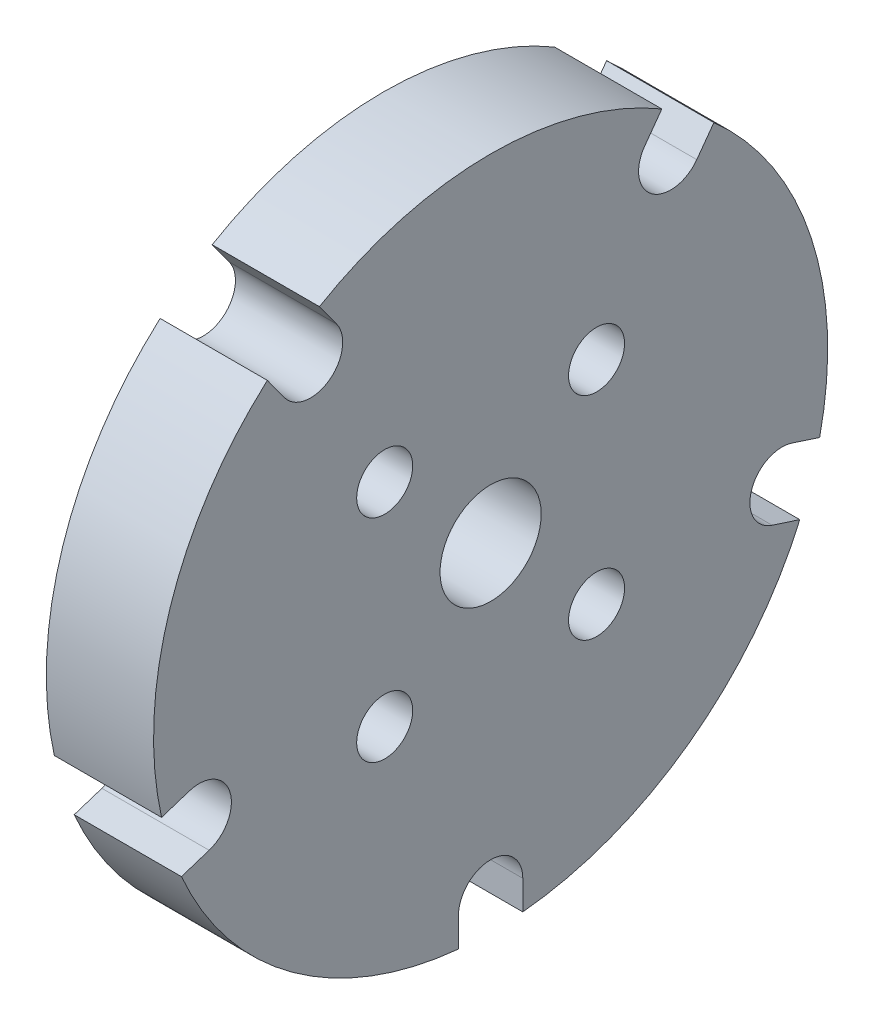
SolidWorks part; units mm, degrees
ref_plane "Plan de face" through (0, 0, 0) normal (0, 0, 1) x (1, 0, 0)
ref_plane "Plan de dessus" through (0, 0, 0) normal (0, 1, 0) x (1, 0, 0)
ref_plane "Plan de droite" through (0, 0, 0) normal (1, 0, 0) x (0, 0, -1)
sketch "Esquisse1" plane through (0, 0, 0) normal (1, 0, 0) x (0, 0, -1)
  circle A0 centre (0, 0) radius 22
  dimension "D1" = 44
extrude "Boss.-Extru.1" add sketch "Esquisse1" along normal blind 7
sketch "Esquisse5" plane through (7, 0, 0) normal (1, 0, 0) x (0, 0, -1)
  line L0 (0, -20) -> (0, -24) construction
  line L1 (2.1, -20) -> (2.1, -24)
  line L2 (-2.1, -20) -> (-2.1, -24)
  line L3 (0, 0) -> (0, -20) construction
  arc A0 (2.1, -20) -> (-2.1, -20) centre (0, -20) ccw
  arc A1 (-2.1, -24) -> (2.1, -24) centre (0, -24) ccw
  circle A2 centre (0, 0) radius 22 construction
  point P3 (0, -22)
  dimension "D2" = 4.2
  dimension "D1" = 20
extrude "Enlèv. mat.-Extru.1" cut sketch "Esquisse5" against normal up to next
pattern_circular "Répétition circulaire1" count 5 over 360 about axis through (0, 0, 0) along (1, 0, 0) of "Enlèv. mat.-Extru.1"
sketch "Esquisse6" plane through (7, 0, 0) normal (1, 0, 0) x (0, 0, -1)
  circle A0 centre (0, 0) radius 3.3
  dimension "D1" = 6.6
extrude "Enlèv. mat.-Extru.2" cut sketch "Esquisse6" against normal up to next
hole_wizard "Chambrage pour vis à tête ronde bombée #61" positions "Esquisse7" profile "Esquisse8" counterbore size "#6" standard "Ansi Inch" end condition through all
sketch "Esquisse7" plane through (0, 0, 0) normal (-1, 0, 0) x (0, 0, 1)
  line L0 (-6.9148, 6.9148) -> (-6.9148, -6.9148) construction
  line L1 (-6.9148, -6.9148) -> (6.9148, -6.9148) construction
  line L2 (6.9148, -6.9148) -> (6.9148, 6.9148) construction
  line L3 (6.9148, 6.9148) -> (-6.9148, 6.9148) construction
  line L5 (0, 6.9148) -> (0, 0) construction
  line L6 (0, 0) -> (-6.9148, 0) construction
  point P0 (-6.9148, 6.9148)
  point P2 (6.9148, 6.9148)
  point P4 (6.9148, -6.9148)
  point P6 (-6.9148, -6.9148)
  dimension "D1" = 19.558
sketch "Esquisse8" plane through (0, 6.9148, -6.9148) normal (0, 1, 0) x (0, 0, 1)
  line L0 (0, 0) -> (0, 7)
  line L1 (0, 7) -> (1.8288, 7)
  line L3 (1.8288, 7) -> (1.8288, 2.4638)
  line L4 (1.8288, 2.4638) -> (3.7706, 2.4638)
  line L5 (3.7706, 2.4638) -> (3.7706, 0)
  line L7 (3.7706, 0) -> (0, 0)
  line L11 (0, -6.35) -> (0, 107.95) construction
  dimension "Diamètre du perçage jusqu'au prochain" = 3.6576
  dimension "Profondeur du perçage jusqu'au prochain" = 7
  dimension "Diamètre du chambrage" = 7.5413
  dimension "Profondeur du chambrage" = 2.4638
